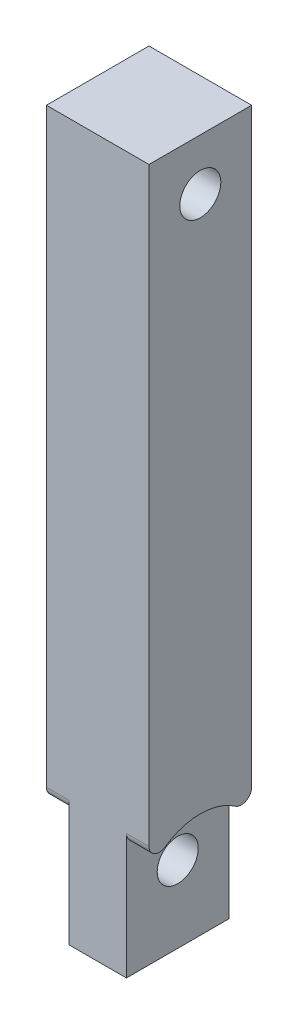
SolidWorks part; units mm, degrees
ref_plane "Front Plane" through (0, 0, 0) normal (0, 0, 1) x (1, 0, 0)
ref_plane "Top Plane" through (0, 0, 0) normal (0, 1, 0) x (1, 0, 0)
ref_plane "Right Plane" through (0, 0, 0) normal (1, 0, 0) x (0, 0, -1)
sketch "Sketch1" plane through (0, 0, 0) normal (0, 1, 0) x (1, 0, 0)
  line L1 (0, 0) -> (-50, 0)
  line L2 (0, 0) -> (0, 50)
  line L3 (0, 50) -> (-50, 50)
  line L4 (-50, 0) -> (-50, 50)
  dimension "D1" = 50
  dimension "D2" = 50
extrude "Boss-Extrude1" add sketch "Sketch1" along normal blind 300
sketch "Sketch2" plane through (0, 0, 0) normal (0, -1, 0) x (1, 0, 0)
  line L0 (-50, 0) -> (0, 0) construction
  line L1 (-39, 0) -> (-11, 0)
  line L2 (-39, 0) -> (-39, -50)
  line L3 (-39, -50) -> (-11, -50)
  line L4 (-11, 0) -> (-11, -50)
  line L5 (0, -50) -> (-50, -50) construction
  line L6 (-50, -50) -> (-50, 0) construction
  line L7 (0, 0) -> (0, -50) construction
  dimension "D1" = 11
  dimension "D2" = 11
extrude "Boss-Extrude2" add sketch "Sketch2" along normal blind 48.9
sketch "Sketch5" plane through (0, 0, 0) normal (1, 0, 0) x (0, 0, -1)
  line L0 (50, 0) -> (0, 0)
  arc A4 (0, 0) -> (50, 0) centre (25, -16.5831) cw
extrude "Cut-Extrude4" cut sketch "Sketch5" against normal up to surface (11 mm away) and the other way through all up to face at (-11, -24.45, -25)
sketch "Sketch6" plane through (-50, 0, 0) normal (-1, 0, 0) x (0, 0, 1)
  line L4 (-50, 0) -> (0, 0)
  arc A2 (-50, 0) -> (0, 0) centre (-25, -16.5831) cw
extrude "Cut-Extrude7" cut sketch "Sketch6" along direction (-1, 0, 0) on the side against the normal up to surface (11 mm away) contours L4 A2
sketch "Sketch12" plane through (-39, 0, 0) normal (-1, 0, 0) x (0, 0, 1)
  line L0 (0, -48.9) -> (0, 0) construction
  circle A0 centre (-25, -11.5831) radius 10
  arc A2 (0, 0) -> (-50, 0) centre (-25, -16.5831) ccw construction
  point P4 (0, 0)
  point P8 (-25, 13.4169)
  dimension "D1" = 20
  dimension "D2" = 25
  dimension "D3" = 25
extrude "Cut-Extrude8" cut sketch "Sketch12" against normal through all
fillet "Fillet2" radius 5 2 edges at (-44.5, 0, 0) (-44.5, 0, -50)
fillet "Fillet3" radius 5 2 edges at (-5.5, 0, -50) (-5.5, 0, 0)
sketch "Sketch13" plane through (0, 0, 0) normal (1, 0, 0) x (0, 0, -1)
  line L0 (0, 300) -> (50, 300) construction
  line L1 (50, 300) -> (50, 12.1397) construction
  circle A0 centre (25, 275) radius 10
  dimension "D1" = 25
  dimension "D2" = 25
extrude "Cut-Extrude9" cut sketch "Sketch13" against normal through all
